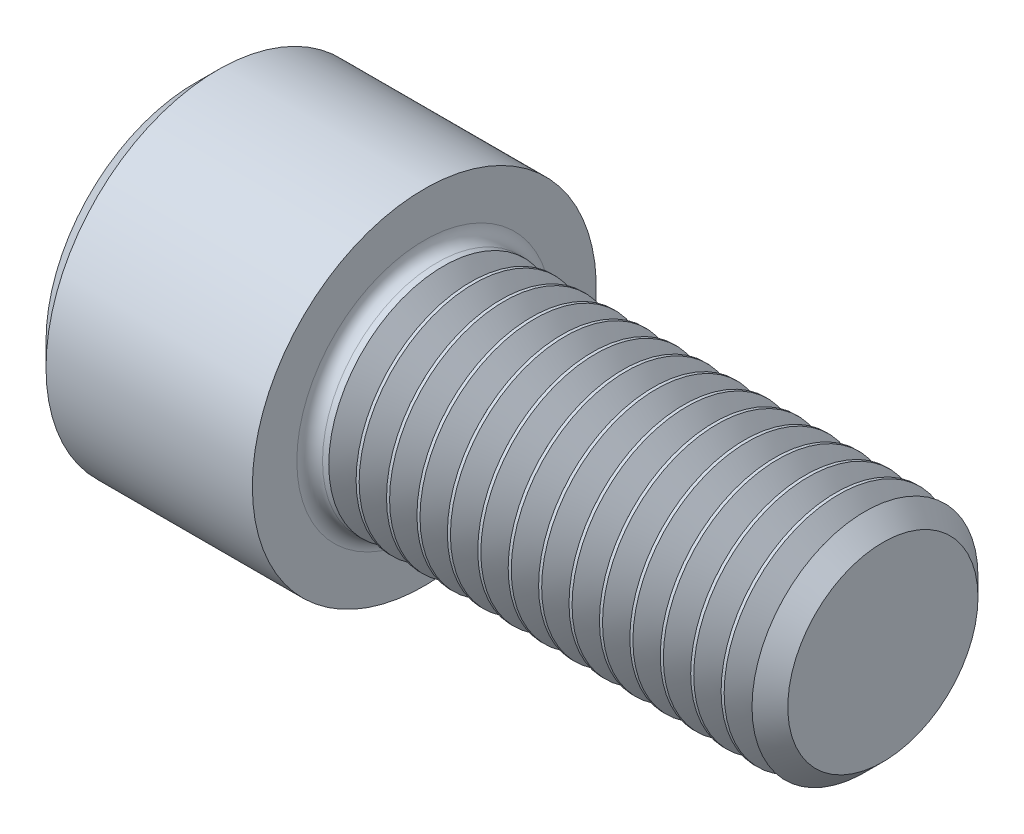
SolidWorks part; units mm, degrees
material "Chrome Stainless Steel"
ref_plane "Front Plane" through (0, 0, 0) normal (0, 0, 1) x (1, 0, 0)
ref_plane "Top Plane" through (0, 0, 0) normal (0, 1, 0) x (1, 0, 0)
ref_plane "Right Plane" through (0, 0, 0) normal (1, 0, 0) x (0, 0, -1)
ref_plane "Plane1" through (0, 0, 0) normal (0, 0, -1) x (-1, 0, 0)
sketch "Sketch1" plane through (0, 0, 0) normal (0, 0, -1) x (-1, 0, 0)
  line L0 (-6.35, 4.7625) -> (-6.35, 0)
  line L1 (-6.35, 0) -> (0, 0)
  line L2 (0, 0) -> (0, 4.7625)
  line L3 (0, 4.7625) -> (-6.35, 4.7625)
  line L4 (-6.35, 0) -> (0, 0) construction
revolve "Revolve1" add sketch "Sketch1" angle 360 about L4
sketch "Sketch2" plane through (6.35, 0, 0) normal (1, 0, 0) x (0, 0, -1)
  circle A0 centre (0, 0) radius 3.175
extrude "Boss-Extrude1" add sketch "Sketch2" along normal blind 0.528
sketch "Sketch3" plane through (6.878, 0, 0) normal (1, 0, 0) x (0, 0, -1)
  circle A0 centre (0, 0) radius 3.175
extrude "Boss-Extrude2" add sketch "Sketch3" along normal blind 0.3788 draft 55
sketch "Sketch4" plane through (7.2568, 0, 0) normal (1, 0, 0) x (0, 0, -1)
  circle A0 centre (0, 0) radius 2.634
extrude "Boss-Extrude3" add sketch "Sketch4" along normal blind 0.3788 draft 55 draft outward yes
sketch "Sketch5" plane through (7.6356, 0, 0) normal (1, 0, 0) x (0, 0, -1)
  circle A0 centre (0, 0) radius 3.175
extrude "Boss-Extrude4" add sketch "Sketch5" along normal blind 0.0847
sketch "Sketch6" plane through (7.7203, 0, 0) normal (1, 0, 0) x (0, 0, -1)
  circle A0 centre (0, 0) radius 3.175
extrude "Boss-Extrude5" add sketch "Sketch6" along normal blind 0.3788 draft 55
sketch "Sketch7" plane through (8.0992, 0, 0) normal (1, 0, 0) x (0, 0, -1)
  circle A0 centre (0, 0) radius 2.634
extrude "Boss-Extrude6" add sketch "Sketch7" along normal blind 0.3788 draft 55 draft outward yes
sketch "Sketch8" plane through (8.478, 0, 0) normal (1, 0, 0) x (0, 0, -1)
  circle A0 centre (0, 0) radius 3.175
extrude "Boss-Extrude7" add sketch "Sketch8" along normal blind 0.0847
sketch "Sketch9" plane through (8.5627, 0, 0) normal (1, 0, 0) x (0, 0, -1)
  circle A0 centre (0, 0) radius 3.175
extrude "Boss-Extrude8" add sketch "Sketch9" along normal blind 0.3788 draft 55
sketch "Sketch10" plane through (8.9415, 0, 0) normal (1, 0, 0) x (0, 0, -1)
  circle A0 centre (0, 0) radius 2.634
extrude "Boss-Extrude9" add sketch "Sketch10" along normal blind 0.3788 draft 55 draft outward yes
sketch "Sketch11" plane through (9.3204, 0, 0) normal (1, 0, 0) x (0, 0, -1)
  circle A0 centre (0, 0) radius 3.175
extrude "Boss-Extrude10" add sketch "Sketch11" along normal blind 0.0847
sketch "Sketch12" plane through (9.4051, 0, 0) normal (1, 0, 0) x (0, 0, -1)
  circle A0 centre (0, 0) radius 3.175
extrude "Boss-Extrude11" add sketch "Sketch12" along normal blind 0.3788 draft 55
sketch "Sketch13" plane through (9.7839, 0, 0) normal (1, 0, 0) x (0, 0, -1)
  circle A0 centre (0, 0) radius 2.634
extrude "Boss-Extrude12" add sketch "Sketch13" along normal blind 0.3788 draft 55 draft outward yes
sketch "Sketch14" plane through (10.1627, 0, 0) normal (1, 0, 0) x (0, 0, -1)
  circle A0 centre (0, 0) radius 3.175
extrude "Boss-Extrude13" add sketch "Sketch14" along normal blind 0.0847
sketch "Sketch15" plane through (10.2474, 0, 0) normal (1, 0, 0) x (0, 0, -1)
  circle A0 centre (0, 0) radius 3.175
extrude "Boss-Extrude14" add sketch "Sketch15" along normal blind 0.3788 draft 55
sketch "Sketch16" plane through (10.6263, 0, 0) normal (1, 0, 0) x (0, 0, -1)
  circle A0 centre (0, 0) radius 2.634
extrude "Boss-Extrude15" add sketch "Sketch16" along normal blind 0.3788 draft 55 draft outward yes
sketch "Sketch17" plane through (11.0051, 0, 0) normal (1, 0, 0) x (0, 0, -1)
  circle A0 centre (0, 0) radius 3.175
extrude "Boss-Extrude16" add sketch "Sketch17" along normal blind 0.0847
sketch "Sketch18" plane through (11.0898, 0, 0) normal (1, 0, 0) x (0, 0, -1)
  circle A0 centre (0, 0) radius 3.175
extrude "Boss-Extrude17" add sketch "Sketch18" along normal blind 0.3788 draft 55
sketch "Sketch19" plane through (11.4686, 0, 0) normal (1, 0, 0) x (0, 0, -1)
  circle A0 centre (0, 0) radius 2.634
extrude "Boss-Extrude18" add sketch "Sketch19" along normal blind 0.3788 draft 55 draft outward yes
sketch "Sketch20" plane through (11.8475, 0, 0) normal (1, 0, 0) x (0, 0, -1)
  circle A0 centre (0, 0) radius 3.175
extrude "Boss-Extrude19" add sketch "Sketch20" along normal blind 0.0847
sketch "Sketch21" plane through (11.9322, 0, 0) normal (1, 0, 0) x (0, 0, -1)
  circle A0 centre (0, 0) radius 3.175
extrude "Boss-Extrude20" add sketch "Sketch21" along normal blind 0.3788 draft 55
sketch "Sketch22" plane through (12.311, 0, 0) normal (1, 0, 0) x (0, 0, -1)
  circle A0 centre (0, 0) radius 2.634
extrude "Boss-Extrude21" add sketch "Sketch22" along normal blind 0.3788 draft 55 draft outward yes
sketch "Sketch23" plane through (12.6898, 0, 0) normal (1, 0, 0) x (0, 0, -1)
  circle A0 centre (0, 0) radius 3.175
extrude "Boss-Extrude22" add sketch "Sketch23" along normal blind 0.0847
sketch "Sketch24" plane through (12.7746, 0, 0) normal (1, 0, 0) x (0, 0, -1)
  circle A0 centre (0, 0) radius 3.175
extrude "Boss-Extrude23" add sketch "Sketch24" along normal blind 0.3788 draft 55
sketch "Sketch25" plane through (13.1534, 0, 0) normal (1, 0, 0) x (0, 0, -1)
  circle A0 centre (0, 0) radius 2.634
extrude "Boss-Extrude24" add sketch "Sketch25" along normal blind 0.3788 draft 55 draft outward yes
sketch "Sketch26" plane through (13.5322, 0, 0) normal (1, 0, 0) x (0, 0, -1)
  circle A0 centre (0, 0) radius 3.175
extrude "Boss-Extrude25" add sketch "Sketch26" along normal blind 0.0847
sketch "Sketch27" plane through (13.6169, 0, 0) normal (1, 0, 0) x (0, 0, -1)
  circle A0 centre (0, 0) radius 3.175
extrude "Boss-Extrude26" add sketch "Sketch27" along normal blind 0.3788 draft 55
sketch "Sketch28" plane through (13.9958, 0, 0) normal (1, 0, 0) x (0, 0, -1)
  circle A0 centre (0, 0) radius 2.634
extrude "Boss-Extrude27" add sketch "Sketch28" along normal blind 0.3788 draft 55 draft outward yes
sketch "Sketch29" plane through (14.3746, 0, 0) normal (1, 0, 0) x (0, 0, -1)
  circle A0 centre (0, 0) radius 3.175
extrude "Boss-Extrude28" add sketch "Sketch29" along normal blind 0.0847
sketch "Sketch30" plane through (14.4593, 0, 0) normal (1, 0, 0) x (0, 0, -1)
  circle A0 centre (0, 0) radius 3.175
extrude "Boss-Extrude29" add sketch "Sketch30" along normal blind 0.3788 draft 55
sketch "Sketch31" plane through (14.8381, 0, 0) normal (1, 0, 0) x (0, 0, -1)
  circle A0 centre (0, 0) radius 2.634
extrude "Boss-Extrude30" add sketch "Sketch31" along normal blind 0.3788 draft 55 draft outward yes
sketch "Sketch32" plane through (15.217, 0, 0) normal (1, 0, 0) x (0, 0, -1)
  circle A0 centre (0, 0) radius 3.175
extrude "Boss-Extrude31" add sketch "Sketch32" along normal blind 0.0847
sketch "Sketch33" plane through (15.3017, 0, 0) normal (1, 0, 0) x (0, 0, -1)
  circle A0 centre (0, 0) radius 3.175
extrude "Boss-Extrude32" add sketch "Sketch33" along normal blind 0.3788 draft 55
sketch "Sketch34" plane through (15.6805, 0, 0) normal (1, 0, 0) x (0, 0, -1)
  circle A0 centre (0, 0) radius 2.634
extrude "Boss-Extrude33" add sketch "Sketch34" along normal blind 0.3788 draft 55 draft outward yes
sketch "Sketch35" plane through (16.0593, 0, 0) normal (1, 0, 0) x (0, 0, -1)
  circle A0 centre (0, 0) radius 3.175
extrude "Boss-Extrude34" add sketch "Sketch35" along normal blind 0.0847
sketch "Sketch36" plane through (16.1441, 0, 0) normal (1, 0, 0) x (0, 0, -1)
  circle A0 centre (0, 0) radius 3.175
extrude "Boss-Extrude35" add sketch "Sketch36" along normal blind 0.3788 draft 55
sketch "Sketch37" plane through (16.5229, 0, 0) normal (1, 0, 0) x (0, 0, -1)
  circle A0 centre (0, 0) radius 2.634
extrude "Boss-Extrude36" add sketch "Sketch37" along normal blind 0.3788 draft 55 draft outward yes
sketch "Sketch38" plane through (16.9017, 0, 0) normal (1, 0, 0) x (0, 0, -1)
  circle A0 centre (0, 0) radius 3.175
extrude "Boss-Extrude37" add sketch "Sketch38" along normal blind 0.0847
sketch "Sketch39" plane through (16.9864, 0, 0) normal (1, 0, 0) x (0, 0, -1)
  circle A0 centre (0, 0) radius 3.175
extrude "Boss-Extrude38" add sketch "Sketch39" along normal blind 0.3788 draft 55
sketch "Sketch40" plane through (17.3653, 0, 0) normal (1, 0, 0) x (0, 0, -1)
  circle A0 centre (0, 0) radius 2.634
extrude "Boss-Extrude39" add sketch "Sketch40" along normal blind 0.3788 draft 55 draft outward yes
sketch "Sketch41" plane through (17.7441, 0, 0) normal (1, 0, 0) x (0, 0, -1)
  circle A0 centre (0, 0) radius 3.175
extrude "Boss-Extrude40" add sketch "Sketch41" along normal blind 0.0847
sketch "Sketch42" plane through (17.8288, 0, 0) normal (1, 0, 0) x (0, 0, -1)
  circle A0 centre (0, 0) radius 3.175
extrude "Boss-Extrude41" add sketch "Sketch42" along normal blind 0.3788 draft 55
sketch "Sketch43" plane through (18.2076, 0, 0) normal (1, 0, 0) x (0, 0, -1)
  circle A0 centre (0, 0) radius 2.634
extrude "Boss-Extrude42" add sketch "Sketch43" along normal blind 0.3469 draft 55 draft outward yes
sketch "Sketch44" plane through (18.5545, 0, 0) normal (1, 0, 0) x (0, 0, -1)
  circle A0 centre (0, 0) radius 3.1294
extrude "Boss-Extrude43" add sketch "Sketch44" along normal blind 0.4955 draft 45
sketch "Sketch45" plane through (0, 0, 0) normal (-1, 0, 0) x (0, 0, 1)
  line L0 (-2.3813, -1.3748) -> (0, -2.7496)
  line L1 (0, -2.7496) -> (2.3813, -1.3748)
  line L2 (2.3813, -1.3748) -> (2.3812, 1.3748)
  line L3 (2.3812, 1.3748) -> (0, 2.7496)
  line L4 (0, 2.7496) -> (-2.3813, 1.3748)
  line L5 (-2.3813, 1.3748) -> (-2.3813, -1.3748)
extrude "Cut-Extrude1" cut sketch "Sketch45" against normal blind 3.048
sketch "Sketch46" plane through (0, 0, 0) normal (0, 0, 1) x (1, 0, 0)
  line L0 (3.048, 2.3813) -> (3.048, 0)
  line L1 (3.048, 0) -> (4.4228, 0)
  line L2 (4.4228, 0) -> (3.048, 2.3813)
  line L3 (3.048, 0) -> (4.4229, 0) construction
revolve "Cut-Revolve1" cut sketch "Sketch46" angle 360 about L3
chamfer "Chamfer1" distance 0.635 angle 45 1 edges at (0, 0, 4.7625)
fillet "Fillet1" radius 0.3556 1 edges at (6.35, 0, -3.175)
